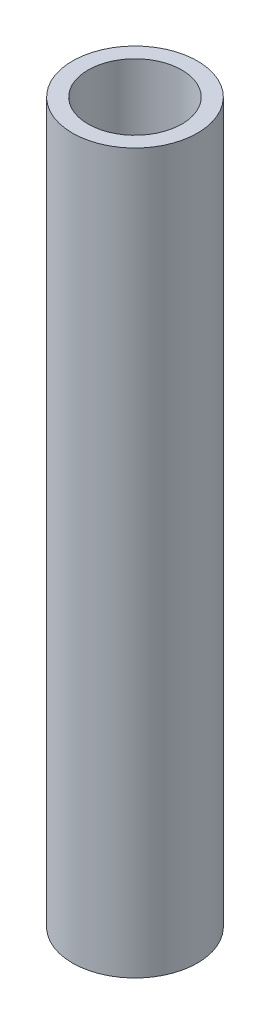
SolidWorks part; units mm, degrees
ref_plane "Front Plane" through (0, 0, 0) normal (0, 0, 1) x (1, 0, 0)
ref_plane "Top Plane" through (0, 0, 0) normal (0, 1, 0) x (1, 0, 0)
ref_plane "Right Plane" through (0, 0, 0) normal (1, 0, 0) x (0, 0, -1)
sketch "Sketch1" plane through (0, 0, 0) normal (0, 1, 0) x (1, 0, 0)
  circle A0 centre (0, 0) radius 4
  circle A1 centre (0, 0) radius 3
  dimension "D1" = 6
  dimension "D2" = 8
extrude "Boss-Extrude1" add sketch "Sketch1" along normal mid plane 46
